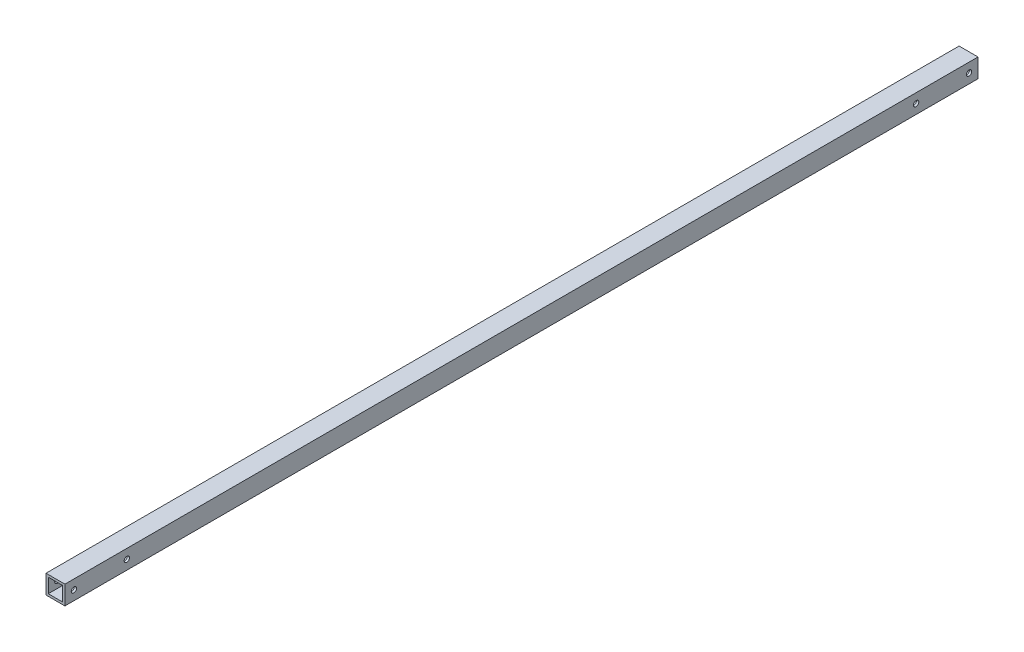
SolidWorks part; units mm, degrees
ref_plane "前视基准面" through (0, 0, 0) normal (0, 0, 1) x (1, 0, 0)
ref_plane "上视基准面" through (0, 0, 0) normal (0, 1, 0) x (1, 0, 0)
ref_plane "右视基准面" through (0, 0, 0) normal (1, 0, 0) x (0, 0, -1)
sketch "草图1" plane through (0, 0, 0) normal (0, 0, 1) x (1, 0, 0)
  line L1 (0, 0) -> (25, 0)
  line L2 (0, 0) -> (0, -25)
  line L3 (0, -25) -> (25, -25)
  line L4 (25, 0) -> (25, -25)
  line L5 (3, -3) -> (22, -3)
  line L6 (3, -3) -> (3, -22)
  line L7 (3, -22) -> (22, -22)
  line L8 (22, -3) -> (22, -22)
  dimension "D1" = 3
  dimension "D2" = 3
  dimension "D3" = 3
  dimension "D4" = 3
  dimension "D5" = 25
  dimension "D6" = 25
extrude "拉伸1" add sketch "草图1" along normal blind 1207.3
hole_wizard "Ø7.0 (7) 直径孔1" positions "草图5" profile "草图4" hole size "Ø7.0" standard "GB"
sketch "草图5" plane through (0, 0, 0) normal (-1, 0, 0) x (0, 0, 1)
  line L1 (0, -25) -> (0, 0) construction
  line L2 (1207.3, -25) -> (0, -25) construction
  point P0 (11.8, -12.5)
  point P1 (81.8, -12.5)
  dimension "D1" = 70
  dimension "D2" = 11.8
  dimension "D3" = 12.5
sketch "草图4" plane through (0, -12.5, 11.8) normal (0, 1, 0) x (0, 0, 1)
  line L0 (0, 0) -> (0, 32.103)
  line L1 (0, 32.103) -> (3.5, 30)
  line L2 (3.5, 30) -> (3.5, 0)
  line L5 (3.5, 0) -> (0, 0)
  line L10 (0, 32.103) -> (-3.5, 30) construction
  line L11 (0, -6.35) -> (0, 107.95) construction
  dimension "孔直径" = 7
  dimension "孔深度" = 30
  dimension "导头角度" = 118
sketch "草图6" plane through (25, 0, 0) normal (1, 0, 0) x (0, 0, -1)
  circle A0 centre (-11.8, -12.5) radius 6
  circle A1 centre (-81.8, -12.5) radius 6
  dimension "D1" = 12
  dimension "D2" = 12
pattern_linear "阵列(线性)1" count 2 spacing 1113.64 along (0, 0, 1) of "Ø7.0 (7) 直径孔1"
